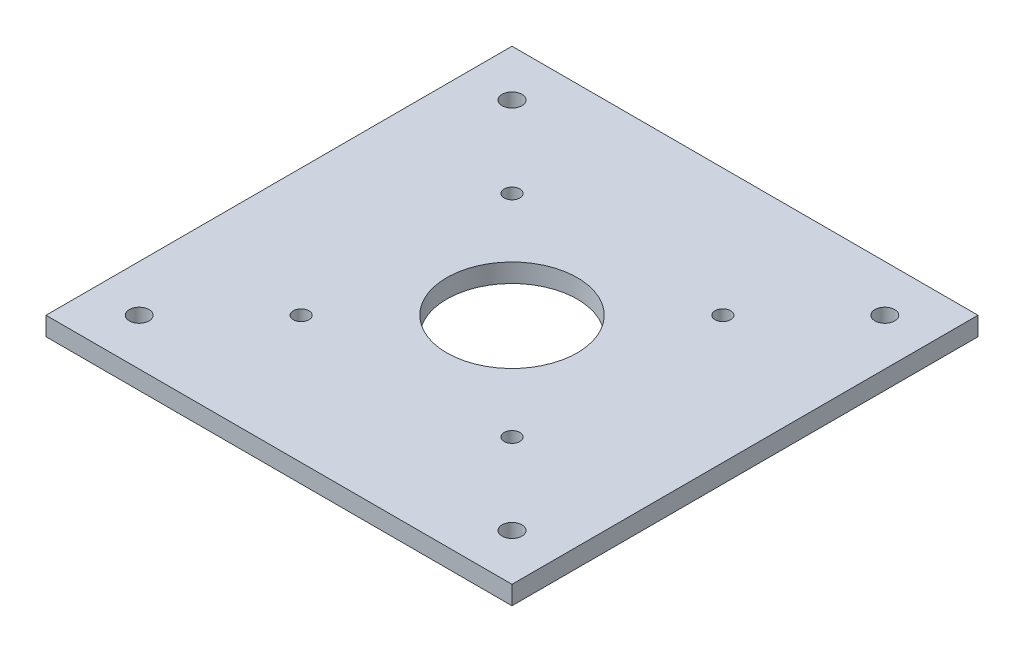
SolidWorks part; units mm, degrees
material "Liga 1060"
ref_plane "Plano frontal" through (0, 0, 0) normal (0, 0, 1) x (1, 0, 0)
ref_plane "Plano superior" through (0, 0, 0) normal (0, 1, 0) x (1, 0, 0)
ref_plane "Plano direito" through (0, 0, 0) normal (1, 0, 0) x (0, 0, -1)
sketch "Esboço1" plane through (0, 0, 0) normal (0, 1, 0) x (1, 0, 0)
  line L1 (-62.5, -62.5) -> (62.5, -62.5)
  line L2 (-62.5, -62.5) -> (-62.5, 62.5)
  line L3 (-62.5, 62.5) -> (62.5, 62.5)
  line L4 (62.5, -62.5) -> (62.5, 62.5)
  line L5 (-62.5, -62.5) -> (62.5, 62.5) construction
  line L6 (-62.5, 62.5) -> (62.5, -62.5) construction
  point P0 (0, 0)
  dimension "D1" = 125
extrude "Ressalto-extrusão1" add sketch "Esboço1" along normal blind 5
sketch "Esboço2" plane through (0, 5, 0) normal (0, 1, 0) x (1, 0, 0)
  circle A0 centre (0, 0) radius 17.5
  dimension "D1" = 35
extrude "Corte-extrusão1" cut sketch "Esboço2" against normal through all
hole_wizard "Broca de rosquear para tarraxa de M51" positions "Esboço4" profile "Esboço5" hole size "M5" standard "ISO" end condition through all
sketch "Esboço4" plane through (0, 5, 0) normal (0, 1, 0) x (1, 0, 0)
  line L1 (-28.2843, -28.2843) -> (28.2843, -28.2843)
  line L2 (-28.2843, -28.2843) -> (-28.2843, 28.2843)
  line L3 (-28.2843, 28.2843) -> (28.2843, 28.2843)
  line L4 (28.2843, -28.2843) -> (28.2843, 28.2843)
  line L5 (-28.2843, -28.2843) -> (28.2843, 28.2843) construction
  line L6 (-28.2843, 28.2843) -> (28.2843, -28.2843) construction
  circle A0 centre (0, 0) radius 40 construction
  point P5 (28.2843, 28.2843)
  point P7 (28.2843, -28.2843)
  point P9 (-28.2843, -28.2843)
  point P11 (-28.2843, 28.2843)
  dimension "D1" = 80
sketch "Esboço5" plane through (28.2843, 5, -28.2843) normal (1, 0, 0) x (0, 0, 1)
  line L0 (0, 0) -> (0, 5)
  line L1 (0, 5) -> (2.1, 5)
  line L2 (2.1, 5) -> (2.1, 0)
  line L5 (2.1, 0) -> (0, 0)
  line L11 (0, -6.35) -> (0, 107.95) construction
  dimension "Thru Hole Dia." = 4.2
  dimension "Thru Hole Depth" = 5
hole_wizard "Broca de rosquear para tarraxa de M5x0.81" positions "Esboço7" profile "Esboço8" hole size "M5x0.8" standard "Ansi Metric"
sketch "Esboço7" plane through (0, 5, 0) normal (0, 1, 0) x (1, 0, 0)
  point P0 (-20, -48)
  point P2 (-20, 48)
  point P4 (20, 48)
  point P6 (20, -48)
  dimension "D1" = 40
  dimension "D2" = 96
  dimension "D3" = 20
  dimension "D4" = 48
sketch "Esboço8" plane through (-20, 5, 48) normal (1, 0, 0) x (0, 0, 1)
  line L0 (0, 0) -> (0, 5)
  line L1 (0, 5) -> (2.1, 5)
  line L2 (2.1, 5) -> (2.1, 0)
  line L5 (2.1, 0) -> (0, 0)
  line L11 (0, -6.35) -> (0, 107.95) construction
  dimension "Thru Hole Dia." = 4.2
  dimension "Thru Hole Depth" = 5
hole_wizard "Furo com folga de M51" positions "Esboço9" profile "Esboço10" hole size "M5" standard "Ansi Metric" end condition through all
sketch "Esboço9" plane through (0, 5, 0) normal (0, 1, 0) x (1, 0, 0)
  point P0 (-50, -50)
  point P2 (-50, 50)
  point P4 (50, 50)
  point P6 (50, -50)
  dimension "D1" = 100
  dimension "D2" = 50
  dimension "D3" = 100
  dimension "D4" = 50
sketch "Esboço10" plane through (-50, 5, 50) normal (1, 0, 0) x (0, 0, 1)
  line L0 (0, 0) -> (0, 5)
  line L1 (0, 5) -> (2.65, 5)
  line L2 (2.65, 5) -> (2.65, 0)
  line L5 (2.65, 0) -> (0, 0)
  line L11 (0, -6.35) -> (0, 107.95) construction
  dimension "Thru Hole Dia." = 5.3
  dimension "Thru Hole Depth" = 5
